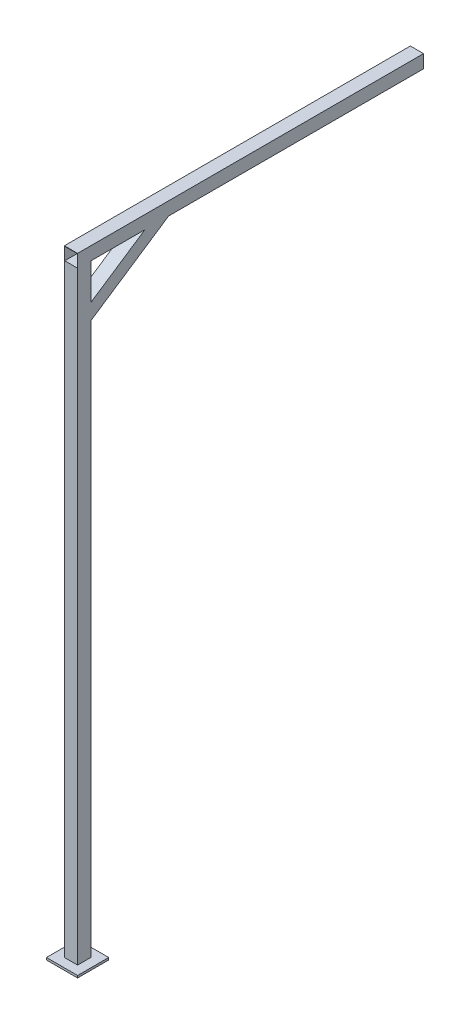
SolidWorks part; units mm, degrees
ref_plane "Alzado" through (0, 0, 0) normal (0, 0, 1) x (1, 0, 0)
ref_plane "Planta" through (0, 0, 0) normal (0, 1, 0) x (1, 0, 0)
ref_plane "Vista lateral" through (0, 0, 0) normal (1, 0, 0) x (0, 0, -1)
sketch "Croquis1" plane through (0, 0, 0) normal (0, 0, 1) x (1, 0, 0)
  line L0 (38.1, 0) -> (38.1, -76.2) construction
  line L1 (0, 0) -> (76.2, 0)
  line L2 (0, 0) -> (0, -76.2)
  line L3 (0, -76.2) -> (76.2, -76.2)
  line L4 (76.2, 0) -> (76.2, -76.2)
  line L6 (1.9, -74.3) -> (74.3, -74.3)
  line L7 (1.9, -74.3) -> (1.9, -1.9)
  line L8 (1.9, -1.9) -> (74.3, -1.9)
  line L9 (74.3, -74.3) -> (74.3, -1.9)
  line L10 (1.9, -74.3) -> (74.3, -1.9) construction
  line L11 (1.9, -1.9) -> (74.3, -74.3) construction
  point P7 (38.1, -38.1)
  dimension "D1" = 76.2
  dimension "D2" = 76.2
  dimension "D3" = 1.9
  dimension "D4" = 1.9
extrude "Saliente-Extruir1" add sketch "Croquis1" along normal blind 2000
sketch "Croquis2" plane through (0, -76.2, 0) normal (0, -1, 0) x (1, 0, 0)
  line L0 (0, 2000) -> (0, 0) construction
  line L1 (76.2, 2000) -> (0, 2000)
  line L2 (76.2, 2000) -> (76.2, 1923.8)
  line L3 (76.2, 1923.8) -> (0, 1923.8)
  line L4 (0, 2000) -> (0, 1923.8)
  line L5 (76.2, 1961.9) -> (0, 1961.9) construction
  line L7 (1.9, 1998.1) -> (74.3, 1998.1)
  line L8 (1.9, 1998.1) -> (1.9, 1925.7)
  line L9 (1.9, 1925.7) -> (74.3, 1925.7)
  line L10 (74.3, 1998.1) -> (74.3, 1925.7)
  line L11 (1.9, 1998.1) -> (74.3, 1925.7) construction
  line L12 (1.9, 1925.7) -> (74.3, 1998.1) construction
  point P9 (38.1, 1961.9)
  dimension "D1" = 76.2
  dimension "D2" = 1.9
  dimension "D3" = 1.9
extrude "Saliente-Extruir2" add sketch "Croquis2" along normal blind 3500
sketch "Croquis3" plane through (0, -3576.2, 0) normal (0, -1, 0) x (1, 0, 0)
  line L0 (74.3, 1961.9) -> (1.9, 1961.9) construction
  line L1 (74.3, 1925.7) -> (74.3, 1998.1) construction
  line L2 (1.9, 1998.1) -> (1.9, 1925.7) construction
  line L4 (-51.9, 1871.9) -> (128.1, 1871.9)
  line L5 (-51.9, 1871.9) -> (-51.9, 2051.9)
  line L6 (-51.9, 2051.9) -> (128.1, 2051.9)
  line L7 (128.1, 1871.9) -> (128.1, 2051.9)
  line L8 (-51.9, 1871.9) -> (128.1, 2051.9) construction
  line L9 (-51.9, 2051.9) -> (128.1, 1871.9) construction
  point P6 (38.1, 1961.9)
  dimension "D1" = 180
  dimension "D2" = 180
extrude "Saliente-Extruir3" add sketch "Croquis3" against normal blind 12.7
sketch "Croquis4" plane through (76.2, 0, 0) normal (1, 0, 0) x (0, 0, -1)
  line L0 (-1473.8, -76.2) -> (-1923.8, -376.2)
  line L1 (-1923.8, -76.2) -> (0, -76.2) construction
  line L2 (-1923.8, -3563.5) -> (-1923.8, -76.2) construction
  line L3 (-1611.1715, -76.2) -> (-1923.8, -284.619)
  line L4 (-1923.8, -376.2) -> (-1923.8, -284.619)
  line L5 (-1473.8, -76.2) -> (-1611.1715, -76.2)
  line L6 (-1516.0682, -12.7978) -> (-1966.0682, -312.7978) construction
  dimension "D1" = 450
  dimension "D2" = 300
  dimension "D3" = 76.2
extrude "Saliente-Extruir4" add sketch "Croquis4" against normal up to surface (76.2 mm away) up to face at (0, -1213.2333, 1307.9333)
